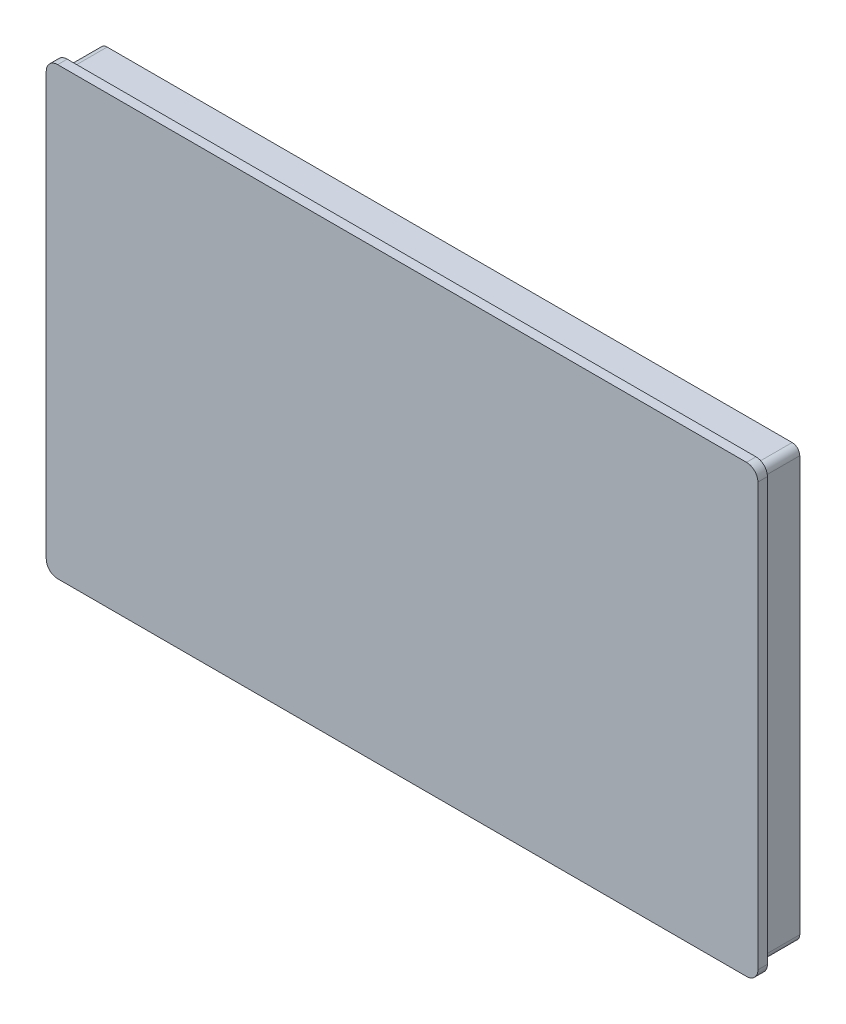
SolidWorks part; units mm, degrees
ref_plane "Piano frontale" through (0, 0, 0) normal (0, 0, 1) x (1, 0, 0)
ref_plane "Piano superiore" through (0, 0, 0) normal (0, 1, 0) x (1, 0, 0)
ref_plane "Piano destro" through (0, 0, 0) normal (1, 0, 0) x (0, 0, -1)
sketch "Schizzo1" plane through (0, 0, 0) normal (0, 0, 1) x (1, 0, 0)
  line L1 (92, -56.5) -> (-92, -56.5)
  line L2 (92, -56.5) -> (92, 56.5)
  line L3 (92, 56.5) -> (-92, 56.5)
  line L4 (-92, -56.5) -> (-92, 56.5)
  line L5 (92, -56.5) -> (-92, 56.5) construction
  line L6 (92, 56.5) -> (-92, -56.5) construction
  point P0 (0, 0)
  dimension "D1" = 184
  dimension "D2" = 113
extrude "Estrusione-Estrusione1" add sketch "Schizzo1" along normal blind 10
fillet "Raccordo1" radius 2 1 edges at (-92, 56.5, 5)
fillet "Raccordo2" radius 2 1 edges at (-92, -56.5, 5)
fillet "Raccordo3" radius 2 1 edges at (92, -56.5, 5)
fillet "Raccordo4" radius 2 1 edges at (92, 56.5, 5)
sketch "Schizzo2" plane through (0, 0, 10) normal (0, 0, 1) x (1, 0, 0)
  line L1 (93.5, -58.5) -> (-93.5, -58.5)
  line L2 (93.5, -58.5) -> (93.5, 58.5)
  line L3 (93.5, 58.5) -> (-93.5, 58.5)
  line L4 (-93.5, -58.5) -> (-93.5, 58.5)
  line L5 (93.5, -58.5) -> (-93.5, 58.5) construction
  line L6 (93.5, 58.5) -> (-93.5, -58.5) construction
  point P0 (0, 0)
  dimension "D1" = 187
  dimension "D2" = 117
extrude "Estrusione-Estrusione2" add sketch "Schizzo2" along normal blind 2.5
fillet "Raccordo5" radius 3 1 edges at (-93.5, 58.5, 11.25)
fillet "Raccordo6" radius 3 1 edges at (-93.5, -58.5, 11.25)
fillet "Raccordo7" radius 3 1 edges at (93.5, -58.5, 11.25)
fillet "Raccordo8" radius 3 1 edges at (93.5, 58.5, 11.25)
